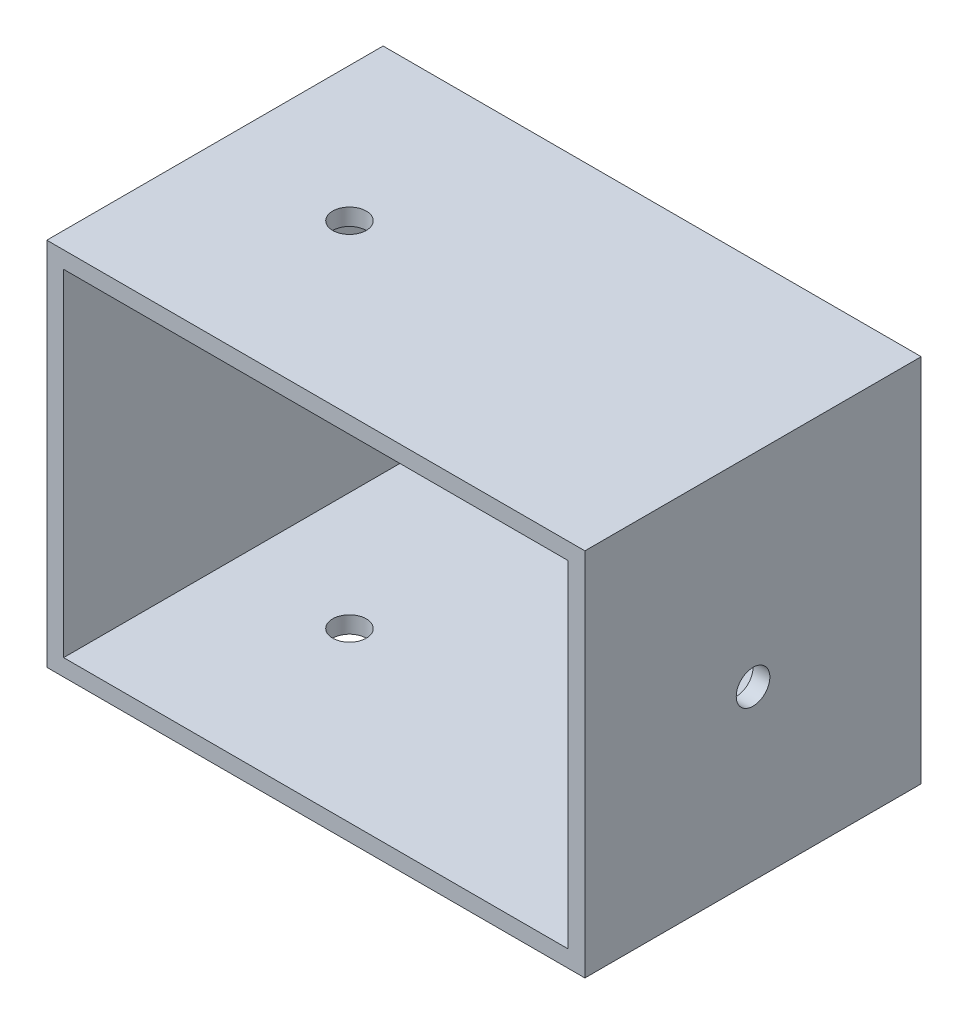
SolidWorks part; units mm, degrees
ref_plane "Front Plane" through (0, 0, 0) normal (0, 0, 1) x (1, 0, 0)
ref_plane "Top Plane" through (0, 0, 0) normal (0, 1, 0) x (1, 0, 0)
ref_plane "Right Plane" through (0, 0, 0) normal (1, 0, 0) x (0, 0, -1)
sketch "Sketch1" plane through (0, 0, 0) normal (0, 0, 1) x (1, 0, 0)
  line L0 (5, -5) -> (155, -5)
  line L1 (0, 0) -> (160, 0)
  line L2 (0, 0) -> (0, -110)
  line L3 (0, -110) -> (160, -110)
  line L4 (160, 0) -> (160, -110)
  line L5 (160, 0) -> (80, 0)
  line L9 (5, -5) -> (5, -105)
  line L10 (5, -105) -> (155, -105)
  line L11 (155, -5) -> (155, -105)
  dimension "160" = 160
  dimension "D2" = 110
  dimension "D5" = 5
extrude "Boss-Extrude1" add sketch "Sketch1" along normal blind 100
sketch "Sketch2" plane through (0, -110, 0) normal (0, -1, 0) x (1, 0, 0)
  line L0 (0, 0) -> (160, 0) construction
  line L1 (0, 100) -> (0, 0) construction
  circle A0 centre (40, 50) radius 5
  dimension "D1" = 50
  dimension "D2" = 40
extrude "Cut-Extrude1" cut sketch "Sketch2" against normal blind 240
sketch "Sketch3" plane through (160, 0, 0) normal (1, 0, 0) x (0, 0, -1)
  line L0 (-100, -110) -> (0, -110) construction
  line L1 (0, 0) -> (0, -110) construction
  circle A0 centre (-50, -60) radius 5
  dimension "D1" = 50
  dimension "D2" = 50
extrude "Cut-Extrude2" cut sketch "Sketch3" against normal blind 10
